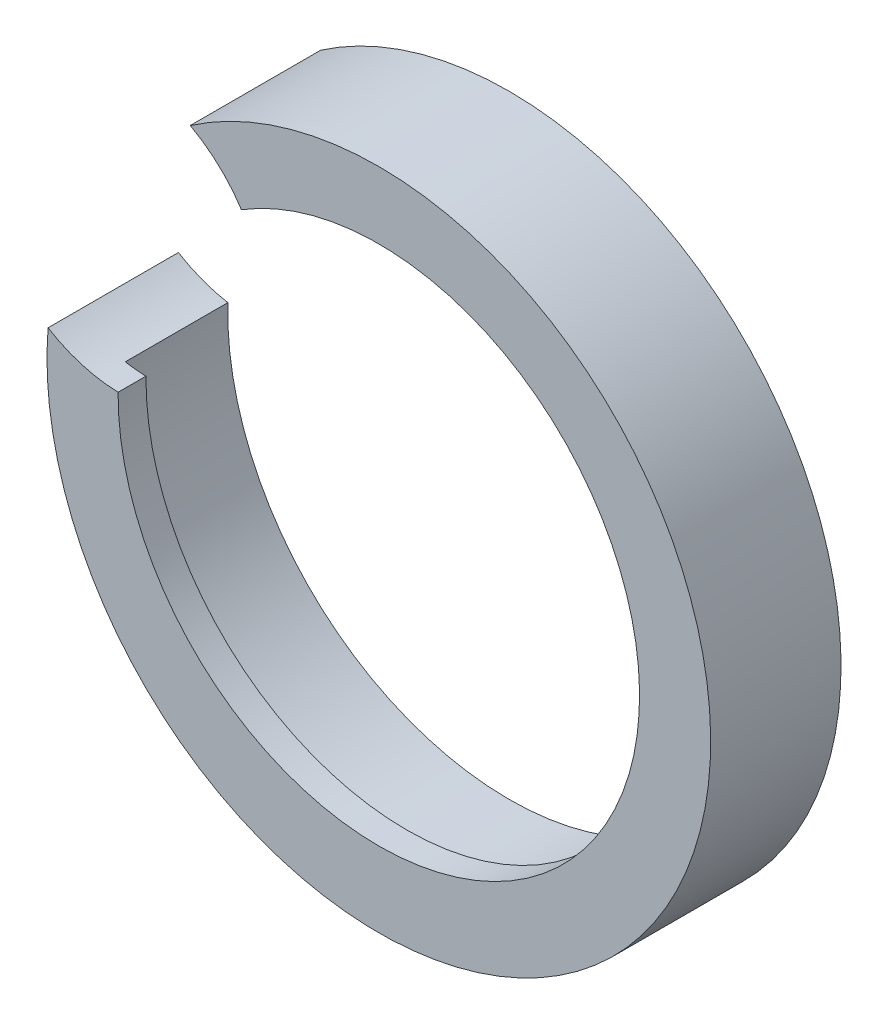
SolidWorks part; units mm, degrees
ref_plane "前视基准面" through (0, 0, 0) normal (0, 0, 1) x (1, 0, 0)
ref_plane "上视基准面" through (0, 0, 0) normal (0, 1, 0) x (1, 0, 0)
ref_plane "右视基准面" through (0, 0, 0) normal (1, 0, 0) x (0, 0, -1)
other "Configuration Table"
sketch "草图1" plane through (0, 0, 0) normal (0, 0, 1) x (1, 0, 0)
  line L0 (0, 0) -> (75.3241, 43.4884) construction
  line L1 (55, 0) -> (-55, 0) construction
  circle A0 centre (0, 0) radius 47.5
  circle A1 centre (0, 0) radius 56
  circle A2 centre (43.3013, 25) radius 12
  dimension "D1" = 95
  dimension "D2" = 112
  dimension "D4" = 24
  dimension "D3" = 30
  dimension "D5" = 50
extrude "凸台-拉伸1" add sketch "草图1" along normal blind 20 contours A1 | A0
sketch "草图3" plane through (0, 0, 20) normal (0, 0, 1) x (1, 0, 0)
  line L0 (0, -11) -> (0, 11) construction
  circle A0 centre (0, 0.6904) radius 44
  circle A2 centre (0, 0) radius 56
  dimension "D1" = 112
  dimension "D2" = 88
sketch "草图4" plane through (0, 0, 0) normal (0, 0, -1) x (-1, 0, 0)
  line L0 (0, 0) -> (92.7086, 53.5253) construction
  line L1 (11, 0) -> (-11, 0) construction
  circle A0 centre (43.3013, 25) radius 24
  dimension "D2" = 48
  dimension "D1" = 30
  dimension "D3" = 50
extrude "凸台-拉伸3" add sketch "草图3" along normal blind 2 and the other way blind 2.7
extrude "切除-拉伸1" cut sketch "草图4" against normal through all
